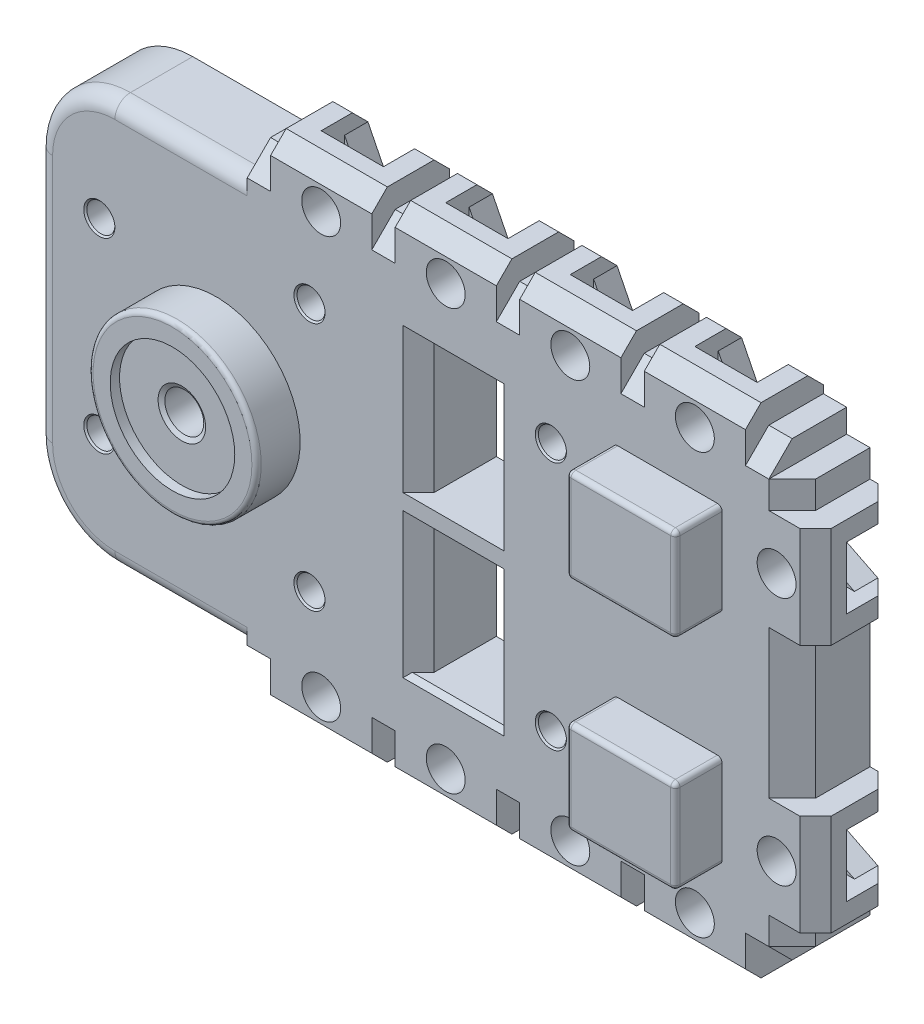
SolidWorks part; units mm, degrees
ref_plane "Front" through (0, 0, 0) normal (0, 0, 1) x (1, 0, 0)
ref_plane "Top" through (0, 0, 0) normal (0, 1, 0) x (1, 0, 0)
ref_plane "Right" through (0, 0, 0) normal (1, 0, 0) x (0, 0, -1)
sketch "Sketch1" plane through (0, 0, 0) normal (0, 0, 1) x (1, 0, 0)
  line L0 (12.75, 0) -> (38.5, 0) construction
  line L1 (37, -13) -> (35.5, -13)
  line L2 (37, -13) -> (37, -11.25)
  line L3 (37, 13) -> (35.5, 13)
  line L4 (-11.5, -13) -> (-11.5, 13)
  line L5 (37, -13) -> (-11.5, 13) construction
  line L6 (37, 13) -> (-11.5, -13) construction
  line L7 (37, -4.75) -> (38.5, -4.75)
  line L8 (38.5, -11.25) -> (38.5, -4.75)
  line L9 (37, -11.25) -> (38.5, -11.25)
  line L10 (37, -4.75) -> (37, 4.75)
  line L11 (2, 13) -> (-11.5, 13)
  line L12 (2, 13) -> (2, 14.5)
  line L13 (35.5, 13) -> (35.5, 14.5)
  line L14 (2, 14.5) -> (3.5, 14.5)
  line L15 (37, 11.25) -> (37, 13)
  line L16 (37, 11.25) -> (38.5, 11.25)
  line L17 (37, 4.75) -> (38.5, 4.75)
  line L18 (38.5, 11.25) -> (38.5, 4.75)
  line L19 (35.5, -13) -> (35.5, -14.5)
  line L20 (34, -14.5) -> (35.5, -14.5)
  line L21 (34, -14.5) -> (34, -16)
  line L22 (34, -16) -> (27.5, -16)
  line L23 (34, 14.5) -> (35.5, 14.5)
  line L24 (34, 14.5) -> (34, 16)
  line L25 (27.5, 14.5) -> (27.5, 16)
  line L26 (34, 16) -> (27.5, 16)
  line L27 (26, 14.5) -> (27.5, 14.5)
  line L28 (26, 14.5) -> (26, 16)
  line L29 (19.5, 14.5) -> (19.5, 16)
  line L30 (26, 16) -> (19.5, 16)
  line L31 (18, 14.5) -> (19.5, 14.5)
  line L32 (18, 14.5) -> (18, 16)
  line L33 (11.5, 14.5) -> (11.5, 16)
  line L34 (18, 16) -> (11.5, 16)
  line L35 (10, 14.5) -> (11.5, 14.5)
  line L36 (10, 14.5) -> (10, 16)
  line L37 (3.5, 14.5) -> (3.5, 16)
  line L38 (10, 16) -> (3.5, 16)
  line L39 (27.5, -14.5) -> (27.5, -16)
  line L40 (26, -14.5) -> (27.5, -14.5)
  line L41 (26, -14.5) -> (26, -16)
  line L42 (26, -16) -> (19.5, -16)
  line L43 (19.5, -14.5) -> (19.5, -16)
  line L44 (18, -14.5) -> (19.5, -14.5)
  line L45 (18, -14.5) -> (18, -16)
  line L46 (18, -16) -> (11.5, -16)
  line L47 (11.5, -14.5) -> (11.5, -16)
  line L48 (10, -14.5) -> (11.5, -14.5)
  line L49 (10, -14.5) -> (10, -16)
  line L50 (10, -16) -> (3.5, -16)
  line L51 (3.5, -14.5) -> (3.5, -16)
  line L52 (2, -14.5) -> (3.5, -14.5)
  line L53 (2, -13) -> (2, -14.5)
  line L54 (2, -13) -> (-11.5, -13)
  point P0 (12.75, 0)
  dimension "D1" = 48.5
  dimension "D2" = 26
  dimension "D3" = 11.5
  dimension "D4" = 1.5
  dimension "D5" = 33.5
  dimension "D6" = 1.5
  dimension "D7" = 1.5
  dimension "D8" = 6.5
  dimension "D9" = 22.5
  dimension "D10" = 1.5
  dimension "D11" = 6.5
  dimension "D12" = 1.5
  dimension "D13" = 1.5
extrude "Boss-Extrude1" add sketch "Sketch1" along normal mid plane 5
sketch "Sketch4" plane through (0, 0, 2.5) normal (0, 0, 1) x (1, 0, 0)
  line L0 (-11.5, 13) -> (-11.5, -13) construction
  line L1 (32.5, -10) -> (-11.5, -10)
  line L2 (32.5, -10) -> (32.5, 10)
  line L3 (32.5, 10) -> (-11.5, 10)
  line L4 (-11.5, -10) -> (-11.5, 10)
  line L5 (32.5, -10) -> (-11.5, 10) construction
  line L6 (32.5, 10) -> (-11.5, -10) construction
  point P0 (10.5, 0)
  dimension "D1" = 20
  dimension "D2" = 44
sketch "Sketch5" plane through (0, 0, 2.5) normal (0, 0, 1) x (1, 0, 0)
  line L1 (32.5, 10) -> (25.5, 10)
  line L2 (32.5, 10) -> (32.5, 4)
  line L3 (25.5, -10) -> (25.5, -4)
  line L4 (25.5, 10) -> (25.5, 4)
  line L5 (32.5, -10) -> (25.5, -10)
  line L6 (37, -4.75) -> (37, 4.75) construction
  line L7 (25.5, 4) -> (32.5, 4)
  line L8 (0, 0) -> (35.7232, 0) construction
  line L9 (32.5, -10) -> (32.5, -4)
  line L10 (25.5, -4) -> (32.5, -4)
  dimension "D2" = 4.5
  dimension "D1" = 7
  dimension "D3" = 20
  dimension "D4" = 8
extrude "Boss-Extrude3" add sketch "Sketch5" along normal blind 3
sketch "Sketch6" plane through (38.5, 0, 0) normal (1, 0, 0) x (0, 0, -1)
  line L0 (2.5, 4.75) -> (2.5, 11.25) construction
  line L1 (-0.5, 10) -> (2.5, 10)
  line L2 (-0.5, 10) -> (-0.5, 6)
  line L3 (-0.5, 6) -> (2.5, 6)
  line L4 (2.5, 10) -> (2.5, 6)
  line L5 (-0.5, 10) -> (2.5, 6) construction
  line L6 (-0.5, 6) -> (2.5, 10) construction
  line L7 (-2.5, 8) -> (1, 8) construction
  line L8 (-2.5, 4.75) -> (-2.5, 11.25) construction
  point P0 (1, 8)
  dimension "D1" = 4
  dimension "D2" = 2
extrude "Cut-Extrude3" cut sketch "Sketch6" against normal blind 1
sketch "Sketch7" plane through (0, 0, 0.5) normal (0, 0, -1) x (-1, 0, 0)
  line L0 (-37.5, 10) -> (-38.5, 10) construction
  line L1 (-37.1547, 10) -> (-38.3094, 8) construction
  line L2 (-38.3094, 8) -> (-37.1547, 6) construction
  line L3 (-37.1547, 6) -> (-34.8453, 6)
  line L6 (-34.8453, 6) -> (-33.6906, 8)
  line L7 (-33.6906, 8) -> (-34.8453, 10)
  line L8 (-34.8453, 10) -> (-37.1547, 10)
  line L9 (-37.5, 8) -> (-36, 8) construction
  line L10 (-37.5, 6) -> (-37.5, 10) construction
  line L11 (-38.5, 10) -> (-38.5, 6) construction
  line L12 (-37.1547, 10) -> (-38.5, 10)
  line L13 (-38.5, 10) -> (-38.5, 6)
  line L14 (-38.5, 6) -> (-37.1547, 6)
  circle A0 centre (-36, 8) radius 2 construction
  dimension "D1" = 2.5
extrude "Cut-Extrude4" cut sketch "Sketch7" along normal blind 1.5
sketch "Sketch8" plane through (0, 0, -2.5) normal (0, 0, -1) x (-1, 0, 0)
  line L0 (-37.5, 10) -> (-35.5, 9)
  line L1 (-35.5, 9) -> (-35.5, 7)
  line L2 (-35.5, 7) -> (-37.5, 6)
  line L3 (-34.8453, 6) -> (-38.5, 6) construction
  line L4 (-37.5, 6) -> (-38.5, 6) construction
  line L5 (-37.5, 8) -> (-35.5, 8) construction
  line L6 (-37.5, 6) -> (-37.5, 10) construction
  line L7 (-37, -4.75) -> (-37, 4.75) construction
  line L8 (-37.5, 10) -> (-37.5, 6)
  dimension "D1" = 2
  dimension "D2" = 1.5
extrude "Cut-Extrude5" cut sketch "Sketch8" against normal up to next
sketch "Sketch10" plane through (0, 16, 0) normal (0, 1, 0) x (1, 0, 0)
  line L0 (28.75, -0.5) -> (28.75, 2.5)
  line L1 (28.75, -0.5) -> (32.75, -0.5)
  line L2 (32.75, -0.5) -> (32.75, 2.5)
  line L3 (28.75, 2.5) -> (32.75, 2.5)
  line L4 (28.75, -0.5) -> (32.75, 2.5) construction
  line L5 (32.75, -0.5) -> (28.75, 2.5) construction
  line L6 (30.75, -2.5) -> (30.75, 1) construction
  line L7 (34, -2.5) -> (27.5, -2.5) construction
  line L8 (34, 2.5) -> (27.5, 2.5) construction
  point P0 (30.75, 1)
  dimension "D1" = 4
  dimension "D2" = 3
extrude "Cut-Extrude6" cut sketch "Sketch10" against normal blind 1
sketch "Sketch11" plane through (0, 0, 0.5) normal (0, 0, -1) x (-1, 0, 0)
  line L0 (-30.75, 16) -> (-30.75, 13.5) construction
  line L1 (-30.75, 15.8094) -> (-32.75, 14.6547) construction
  line L2 (-32.75, 14.6547) -> (-32.75, 12.3453)
  line L3 (-32.75, 12.3453) -> (-30.75, 11.1906)
  line L4 (-30.75, 11.1906) -> (-28.75, 12.3453)
  line L5 (-28.75, 12.3453) -> (-28.75, 14.6547)
  line L6 (-28.75, 14.6547) -> (-30.75, 15.8094) construction
  line L7 (-28.75, 16) -> (-32.75, 16) construction
  line L8 (-34, 16) -> (-32.75, 16) construction
  line L9 (-28.75, 14.6547) -> (-28.75, 16)
  line L10 (-28.75, 16) -> (-32.75, 16)
  line L11 (-32.75, 16) -> (-32.75, 14.6547)
  line L12 (-32.5, 10) -> (-25.5, 10) construction
  line L13 (-25.5, 10) -> (-25.5, 4) construction
  circle A0 centre (-30.75, 13.5) radius 2 construction
  dimension "D1" = 4
  dimension "D2" = 2.5
extrude "Cut-Extrude7" cut sketch "Sketch11" along normal blind 1.5
sketch "Sketch12" plane through (0, 0, -2.5) normal (0, 0, -1) x (-1, 0, 0)
  line L0 (-28.75, 15) -> (-29.75, 13)
  line L1 (-29.75, 13) -> (-31.75, 13)
  line L2 (-31.75, 13) -> (-32.75, 15)
  line L3 (-30.75, 15) -> (-30.75, 13) construction
  line L4 (-32.75, 15) -> (-28.75, 15) construction
  line L5 (-35.5, 14.5) -> (-34, 14.5) construction
  line L6 (-32.75, 15) -> (-28.75, 15)
  dimension "D1" = 1.5
  dimension "D2" = 2
extrude "Cut-Extrude8" cut sketch "Sketch12" against normal up to next
sketch "Sketch13" plane through (0, 0, 2.5) normal (0, 0, 1) x (1, 0, 0)
  circle A0 centre (36, 8) radius 1.25
  dimension "D1" = 2.5
extrude "Cut-Extrude9" cut sketch "Sketch13" against normal up to next
sketch "Sketch14" plane through (0, 0, 2.5) normal (0, 0, 1) x (1, 0, 0)
  circle A0 centre (30.75, 13.5) radius 1.25
  dimension "D1" = 2.5
extrude "Cut-Extrude10" cut sketch "Sketch14" against normal up to next
pattern_linear "LPattern1" count 4 spacing 8 along (-1, 0, 0) of "Cut-Extrude6", "Cut-Extrude7", "Cut-Extrude8", "Cut-Extrude10"
mirror "Mirror1" about plane through (0, 0, 0) normal (0, 1, 0) of "LPattern1", "Cut-Extrude10", "Cut-Extrude9", "Cut-Extrude8", "Cut-Extrude7", "Cut-Extrude6", "Cut-Extrude5", "Cut-Extrude4", "Cut-Extrude3"
fillet "Fillet1" radius 5 2 edges at (-11.5, -13, 0) (-11.5, 13, 0)
sketch "Sketch15" plane through (0, 0, 2.5) normal (0, 0, 1) x (1, 0, 0)
  line L0 (0, 0) -> (38.4863, 0) construction
  line L1 (38.5, 4.75) -> (38.5, 11.25) construction
  line L3 (-7.25, 9.25) -> (-7.25, 14.1999)
  line L4 (-7.25, 14.1999) -> (-13.5472, 14.1999)
  line L5 (-13.5472, 14.1999) -> (-13.5472, 7.5)
  line L6 (-13.5472, 7.5) -> (-9, 7.5)
  line L7 (-13.5472, -14.1999) -> (-13.5472, -7.5)
  line L8 (-7.25, -14.1999) -> (-13.5472, -14.1999)
  line L9 (-7.25, -9.25) -> (-7.25, -14.1999)
  line L10 (-13.5472, -7.5) -> (-9, -7.5)
  line L11 (-11.5, -10) -> (-11.5, 10) construction
  circle A0 centre (33, 10.4) radius 1.75
  circle A1 centre (33, -10.4) radius 1.75
  arc A2 (-9, 7.5) -> (-7.25, 9.25) centre (-9, 9.25) ccw
  circle A3 centre (33, -10.4) radius 1.75
  arc A4 (-9, -7.5) -> (-7.25, -9.25) centre (-9, -9.25) cw
  dimension "D1" = 20.8
  dimension "D2" = 5.5
  dimension "D3" = 3.5
  dimension "D4" = 18.5
  dimension "D5" = 2.5
sketch "Sketch2" plane through (0, 0, 2.5) normal (0, 0, 1) x (1, 0, 0)
  line L0 (0, 0) -> (23.4398, 0) construction
  line L1 (13, 9.5) -> (17.5, 9.5)
  line L2 (13, 9.5) -> (13, 0.5)
  line L3 (13, 0.5) -> (17.5, 0.5)
  line L4 (17.5, 9.5) -> (17.5, 0.5)
  line L5 (13, 9.5) -> (17.5, 0.5) construction
  line L6 (13, 0.5) -> (17.5, 9.5) construction
  line L7 (13, -9.5) -> (13, -0.5)
  line L8 (13, -9.5) -> (17.5, -9.5)
  line L9 (17.5, -9.5) -> (17.5, -0.5)
  line L10 (13, -0.5) -> (17.5, -0.5)
  point P0 (15.25, 5)
  dimension "D1" = 4.5
  dimension "D2" = 9
  dimension "D3" = 13
  dimension "D4" = 19
extrude "Cut-Extrude1" cut sketch "Sketch2" against normal through all
sketch "Sketch3" plane through (0, 0, 2.5) normal (0, 0, 1) x (1, 0, 0)
  circle A0 centre (0, 0) radius 5.4
  dimension "D1" = 10.8
extrude "Boss-Extrude4" add sketch "Sketch3" along normal blind 2.8
sketch "Sketch17" plane through (0, 0, 5.3) normal (0, 0, 1) x (1, 0, 0)
  circle A0 centre (0, 0) radius 4
  dimension "D1" = 8
extrude "Cut-Extrude13" cut sketch "Sketch17" against normal blind 0.6
hole_wizard "Ø1.6 (1.6) Diameter Hole1" positions "Sketch19" profile "Sketch18" hole size "Ø1.6" standard "ISO"
sketch "Sketch19" plane through (0, 0, -2.5) normal (0, 0, -1) x (-1, 0, 0)
  point P0 (-33, 10.4)
  point P3 (-33, -10.4)
  point P6 (9, 9.25)
  point P9 (9, -9.25)
sketch "Sketch18" plane through (33, 10.4, -2.5) normal (1, 0, 0) x (0, 1, 0)
  line L0 (0, 0) -> (0, 4.9807)
  line L1 (0, 4.9807) -> (0.8, 4.5)
  line L2 (0.8, 4.5) -> (0.8, 0.0577)
  line L3 (0.8, 0.0577) -> (0.9, 0)
  line L5 (0.9, 0) -> (0, 0)
  line L6 (-0.8, 0.0577) -> (-0.9, 0) construction
  line L10 (0, 4.9807) -> (-0.8, 4.5) construction
  line L11 (0, -6.35) -> (0, 107.95) construction
  dimension "Hole Dia." = 1.6
  dimension "Hole Depth" = 4.5
  dimension "Near C'Sink Dia." = 1.8
  dimension "Near C'Sink Angle" = 120
  dimension "Drill Angle" = 118
hole_wizard "M3 Tapped Hole1" positions "Sketch21" profile "Sketch22" tap size "M3" standard "ISO" end condition through all
sketch "Sketch21" plane through (0, 0, 4.7) normal (0, 0, 1) x (1, 0, 0)
  point P0 (0, 0)
sketch "Sketch22" plane through (0, 0, 4.7) normal (1, 0, 0) x (0, -1, 0)
  line L0 (0, 0) -> (0, 7.2)
  line L1 (0, 7.2) -> (1.25, 7.2)
  line L2 (1.25, 7.2) -> (1.25, 0.1588)
  line L3 (1.25, 0.1588) -> (1.525, 0)
  line L5 (1.525, 0) -> (0, 0)
  line L6 (-1.25, 0.1588) -> (-1.525, 0) construction
  line L11 (0, -6.35) -> (0, 107.95) construction
  dimension "Thru Tap Drill Dia." = 2.5
  dimension "Thru Tap Drill Depth" = 7.2
  dimension "Near C'Sink Dia." = 3.05
  dimension "Near C'Sink Angle" = 120
cosmetic thread "Hole Thread1" parameters "D2"=3
hole_wizard "Ø1.8 (1.8) Diameter Hole1" positions "Sketch24" profile "Sketch25" hole size "Ø1.8" standard "ISO" end condition through all
sketch "Sketch24" plane through (0, 0, 2.5) normal (0, 0, 1) x (1, 0, 0)
  line L0 (0, 0) -> (35.0384, 0) construction
  point P0 (6, 8)
  point P7 (21.5, 8)
  point P9 (-7.5, 6)
  point P14 (21.5, -8)
  point P15 (6, -8)
  point P16 (-7.5, -6)
  dimension "D1" = 16
  dimension "D2" = 6
  dimension "D3" = 15.5
  dimension "D4" = 12
  dimension "D5" = 7.5
sketch "Sketch25" plane through (6, 8, 2.5) normal (1, 0, 0) x (0, -1, 0)
  line L0 (0, 0) -> (0, 5)
  line L1 (0, 5) -> (0.9, 5)
  line L2 (0.9, 5) -> (0.9, 0.1)
  line L3 (0.9, 0.1) -> (1, 0)
  line L5 (1, 0) -> (0, 0)
  line L6 (-0.9, 0.1) -> (-1, 0) construction
  line L11 (0, -6.35) -> (0, 107.95) construction
  dimension "Thru Hole Dia." = 1.8
  dimension "Thru Hole Depth" = 5
  dimension "Near C'Sink Dia." = 2
  dimension "Near C'Sink Angle" = 90
fillet "Fillet2" radius 1 5 edges at (-2.25, 13, 2.5) (-10.0355, 11.5355, 2.5) (-11.5, 0, 2.5) (-10.0355, -11.5355, 2.5) (-2.25, -13, 2.5)
chamfer "Chamfer1" distance 1 angle 45 30 edges at (4.125, -16, -2.5) (9.375, -16, -2.5) (12.125, -16, -2.5) (17.375, -16, -2.5) (20.125, -16, -2.5) (25.375, -16, -2.5) (28.125, -16, -2.5) (33.375, -16, -2.5) (4.125, 16, -2.5) (9.375, 16, -2.5) (12.125, 16, -2.5) (17.375, 16, -2.5) (20.125, 16, -2.5) (25.375, 16, -2.5) (28.125, 16, -2.5) (33.375, 16, -2.5) (38.5, -10.625, -2.5) (38.5, -5.375, -2.5) (38.5, 5.375, -2.5) (38.5, 10.625, -2.5) (6.75, 16, 2.5) (14.75, 16, 2.5) (22.75, 16, 2.5) (30.75, 16, 2.5) (38.5, 8, 2.5) (38.5, -8, 2.5) (30.75, -16, 2.5) (22.75, -16, 2.5) (14.75, -16, 2.5) (6.75, -16, 2.5)
chamfer "Chamfer2" distance 1.5 angle 45 13 edges at (2.75, 14.5, 2.5) (10.75, 14.5, 2.5) (18.75, 14.5, 2.5) (26.75, 14.5, 2.5) (34.75, 14.5, 2.5) (37, 12.125, 2.5) (2.75, -14.5, 2.5) (10.75, -14.5, 2.5) (18.75, -14.5, 2.5) (26.75, -14.5, 2.5) (37, -12.125, 2.5) (34.75, -14.5, 2.5) (37, 0, 2.5)
chamfer "Chamfer3" distance 1 angle 45 4 edges at (13, 5, 2.5) (17.5, 5, 2.5) (17.5, -5, 2.5) (13, -5, 2.5)
chamfer "Chamfer4" distance 0.3 angle 45 2 edges at (15.25, 9.5, 2.5) (15.25, -9.5, 2.5)
fillet "Fillet3" radius 0.3 17 edges at (29, 4, 5.5) (25.5, 7, 5.5) (29, 10, 5.5) (32.5, 7, 5.5) (25.5, -7, 5.5) (29, -4, 5.5) (32.5, -7, 5.5) (29, -10, 5.5) (5.4, 0, 5.3) (25.5, 10, 4) (32.5, 10, 4) (32.5, 4, 4) (25.5, 4, 4) (25.5, -4, 4) (32.5, -4, 4) (32.5, -10, 4) (25.5, -10, 4)
